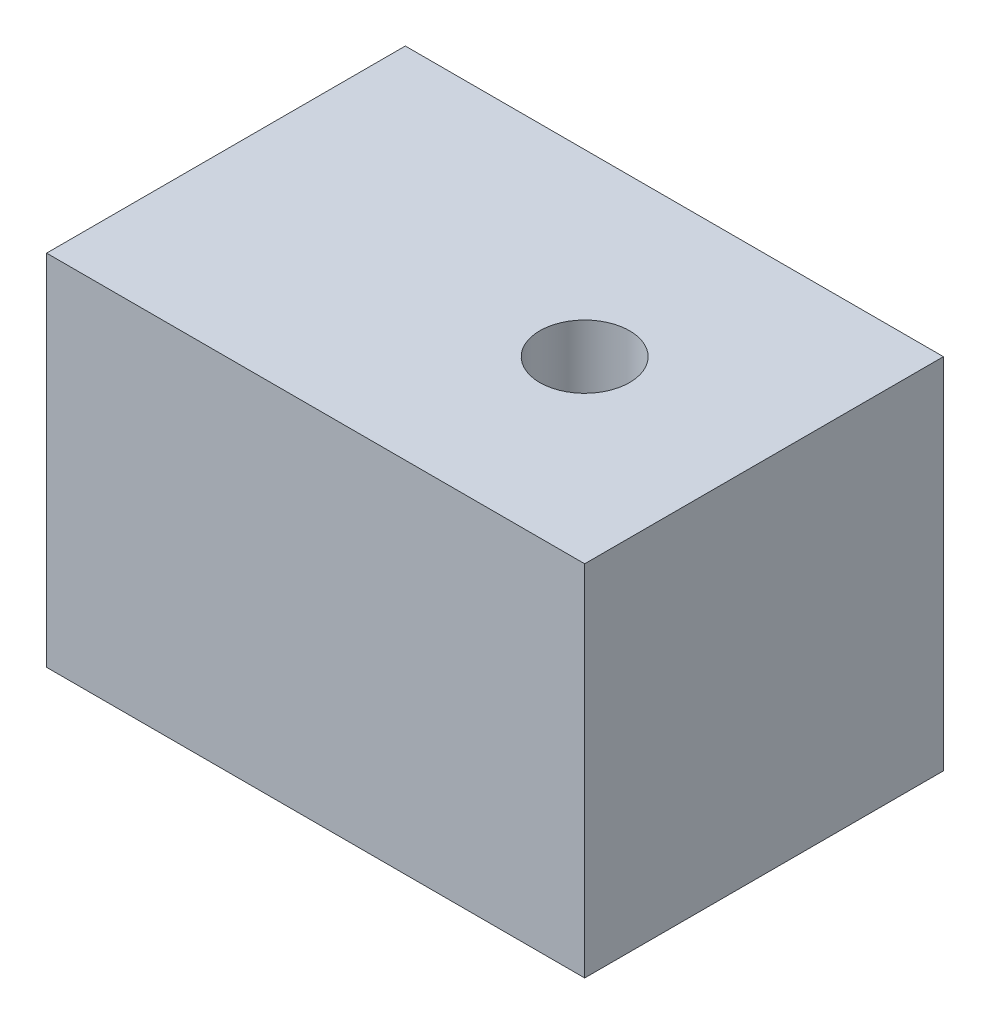
SolidWorks part; units mm, degrees
ref_plane "Front Plane" through (0, 0, 0) normal (0, 0, 1) x (1, 0, 0)
ref_plane "Top Plane" through (0, 0, 0) normal (0, 1, 0) x (1, 0, 0)
ref_plane "Right Plane" through (0, 0, 0) normal (1, 0, 0) x (0, 0, -1)
sketch "Sketch1" plane through (0, 0, 0) normal (0, 1, 0) x (1, 0, 0)
  line L1 (-19.05, -12.7) -> (19.05, -12.7)
  line L2 (-19.05, -12.7) -> (-19.05, 12.7)
  line L3 (-19.05, 12.7) -> (19.05, 12.7)
  line L4 (19.05, -12.7) -> (19.05, 12.7)
  line L5 (-19.05, -12.7) -> (19.05, 12.7) construction
  line L6 (-19.05, 12.7) -> (19.05, -12.7) construction
  point P0 (0, 0)
extrude "Boss-Extrude1" add sketch "Sketch1" along normal blind 25.4
sketch "Sketch2" plane through (0, 25.4, 0) normal (0, 1, 0) x (1, 0, 0)
  line L1 (19.05, -12.7) -> (19.05, 12.7) construction
  line L2 (19.05, 0) -> (6.35, 0) construction
  circle A0 centre (6.35, 0) radius 3.18
sketch "Sketch3" plane through (-19.05, 0, 0) normal (-1, 0, 0) x (0, 0, 1)
  line L0 (0, 0) -> (0, 25.4) construction
  line L1 (-12.7, 25.4) -> (12.7, 25.4) construction
  line L2 (12.7, 12.7) -> (-12.7, 12.7) construction
  line L3 (12.7, 25.4) -> (12.7, 0) construction
  line L4 (-12.7, 25.4) -> (-12.7, 0) construction
  circle A0 centre (0, 12.7) radius 1.5875
extrude "Cut-Extrude2" cut sketch "Sketch3" against normal blind 25.4
hole_wizard "1/4-28 Tapped Hole1" positions "Sketch5" profile "Sketch4" tap size "1/4-28" standard "ANSI Inch"
sketch "Sketch5" plane through (-19.05, 0, 0) normal (-1, 0, 0) x (0, 0, 1)
  point P0 (0, 12.7)
sketch "Sketch4" plane through (-19.05, 12.7, 0) normal (0, 1, 0) x (0, 0, 1)
  line L0 (0, 0) -> (0, 18.8554)
  line L1 (0, 18.8554) -> (2.7051, 17.23)
  line L2 (2.7051, 17.23) -> (2.7051, 0)
  line L5 (2.7051, 0) -> (0, 0)
  line L10 (0, 18.8554) -> (-2.7051, 17.23) construction
  line L11 (0, -6.35) -> (0, 107.95) construction
  dimension "Tap Drill Dia." = 5.4102
  dimension "Tap Drill Depth" = 17.23
  dimension "Drill Angle" = 118
cosmetic thread "Hole Thread1" parameters "D1"=12.7, "D2"=6.35
extrude "Cut-Extrude6" cut sketch "Sketch2" against normal blind 15.875 contours A0
sketch "Sketch8" plane through (0, 0, 0) normal (0, -1, 0) x (1, 0, 0)
  circle A0 centre (6.35, 0) radius 1.5875
extrude "Cut-Extrude7" cut sketch "Sketch8" against normal through all
